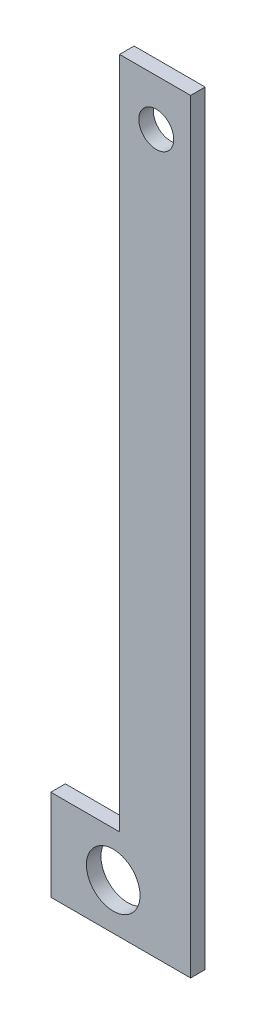
SolidWorks part; units mm, degrees
material "Copper"
ref_plane "Front Plane" through (0, 0, 0) normal (0, 0, 1) x (1, 0, 0)
ref_plane "Top Plane" through (0, 0, 0) normal (0, 1, 0) x (1, 0, 0)
ref_plane "Right Plane" through (0, 0, 0) normal (1, 0, 0) x (0, 0, -1)
sketch "Sketch1" plane through (0, 0, 0) normal (0, 0, 1) x (1, 0, 0)
  line L1 (3.6662, -17.8872) -> (18.3465, -17.8872)
  line L2 (3.6662, -17.8872) -> (3.6662, -156.9401)
  line L3 (3.6662, -175.7338) -> (18.3465, -175.7338)
  line L4 (18.3465, -17.8872) -> (18.3465, -175.7338)
  line L5 (18.3465, -175.7338) -> (-10.5267, -175.7338)
  line L6 (18.3465, -175.7338) -> (18.3465, -156.9401)
  line L7 (3.6662, -156.9401) -> (-10.5267, -156.9401)
  line L8 (-10.5267, -175.7338) -> (-10.5267, -156.9401)
  circle A0 centre (2.3572, -166.2255) radius 5.5369
  circle A1 centre (11.25, -27.5) radius 3.6041
  spline S0 degree 3 poles (-15.0709, -160.1991) (-14.9513, -160.0933) (-14.7122, -159.8816) (-14.3464, -159.5727) (-13.9753, -159.2701) (-13.5986, -158.9744) (-13.0254, -158.5414) (-12.2428, -157.9887) (-11.2337, -157.3438) (-10.1961, -156.7459) (-8.7777, -156.0135) (-6.9435, -155.2216) (-4.6649, -154.4779) (-2.3275, -153.9468) (0.0488, -153.633) (2.4439, -153.539) (4.8375, -153.6657) (7.2093, -154.012) (9.5393, -154.5749) (11.8075, -155.3497) (13.6306, -156.1667) (15.039, -156.9184) (16.0683, -157.5304) (17.0684, -158.1891) (17.9296, -158.8148) (18.6611, -159.3911) (19.2738, -159.9028) (19.6686, -160.2595) (19.8661, -160.4379) knots 0 0 0 0 0.012507 0.025008 0.037507 0.050007 0.062515 0.093769 0.125024 0.156279 0.187534 0.250028 0.312521 0.375014 0.437507 0.500001 0.562494 0.624987 0.687481 0.749974 0.812467 0.843722 0.874977 0.906232 0.937487 0.958328 0.979159 1 1 1 1 construction
extrude "Boss-Extrude1" add sketch "Sketch1" along normal blind 3 contours L8 L5 L3 L4 L1 L2 L7 A1 A0
